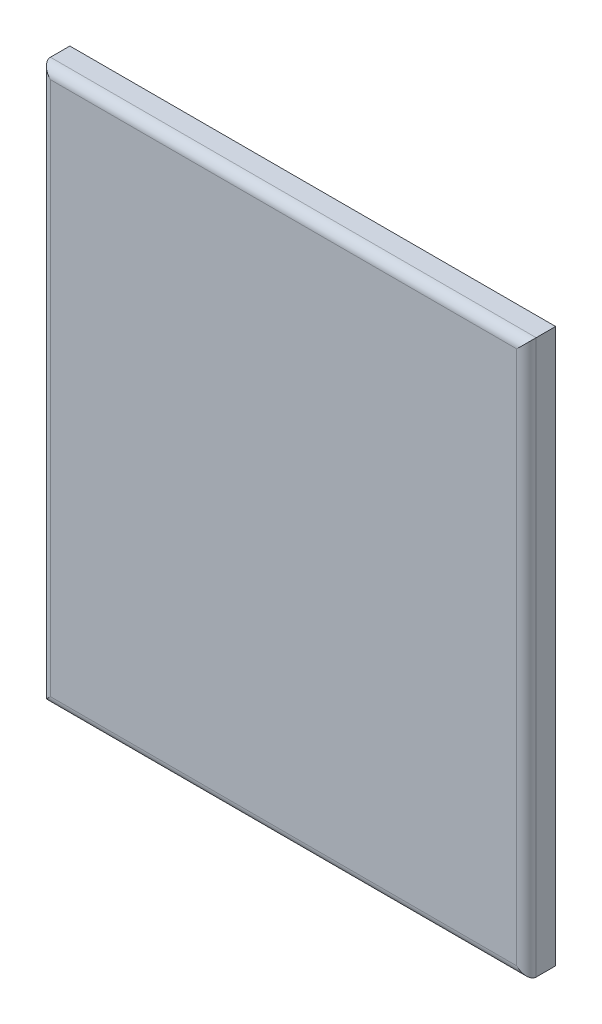
SolidWorks part; units mm, degrees
ref_plane "Front Plane" through (0, 0, 0) normal (0, 0, 1) x (1, 0, 0)
ref_plane "Top Plane" through (0, 0, 0) normal (0, 1, 0) x (1, 0, 0)
ref_plane "Right Plane" through (0, 0, 0) normal (1, 0, 0) x (0, 0, -1)
sketch "Sketch1" plane through (0, 0, 0) normal (0, 0, 1) x (1, 0, 0)
  line L1 (0, 0) -> (-500, 0)
  line L2 (0, 0) -> (0, -570)
  line L3 (0, -570) -> (-500, -570)
  line L4 (-500, 0) -> (-500, -570)
  dimension "D1" = 570
  dimension "D2" = 500
extrude "Boss-Extrude1" add sketch "Sketch1" along normal blind 30
fillet "Fillet1" radius 10 4 edges at (-500, -285, 30) (-250, -570, 30) (0, -285, 30) (-250, 0, 30)
